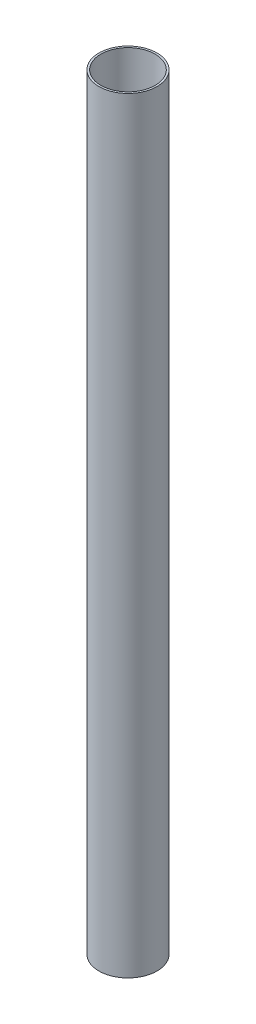
SolidWorks part; units mm, degrees
material "E-Glass Fiber"
ref_plane "Front Plane" through (0, 0, 0) normal (0, 0, 1) x (1, 0, 0)
ref_plane "Top Plane" through (0, 0, 0) normal (0, 1, 0) x (1, 0, 0)
ref_plane "Right Plane" through (0, 0, 0) normal (1, 0, 0) x (0, 0, -1)
sketch "Sketch1" plane through (0, 0, 0) normal (0, 0, 1) x (1, 0, 0)
  line L0 (0, 0) -> (0, -40.98) construction
  line L1 (28.9179, 40.3862) -> (28.9179, -721.6138) construction
  line L2 (26.9875, 40.3862) -> (28.9179, 40.3862)
  line L3 (26.9875, 40.3862) -> (26.9875, -721.6138)
  line L4 (26.9875, -721.6138) -> (28.9179, -721.6138)
  line L5 (28.9179, 40.3862) -> (28.9179, -721.6138)
revolve "Revolve1" add sketch "Sketch1" angle 360 about L0
